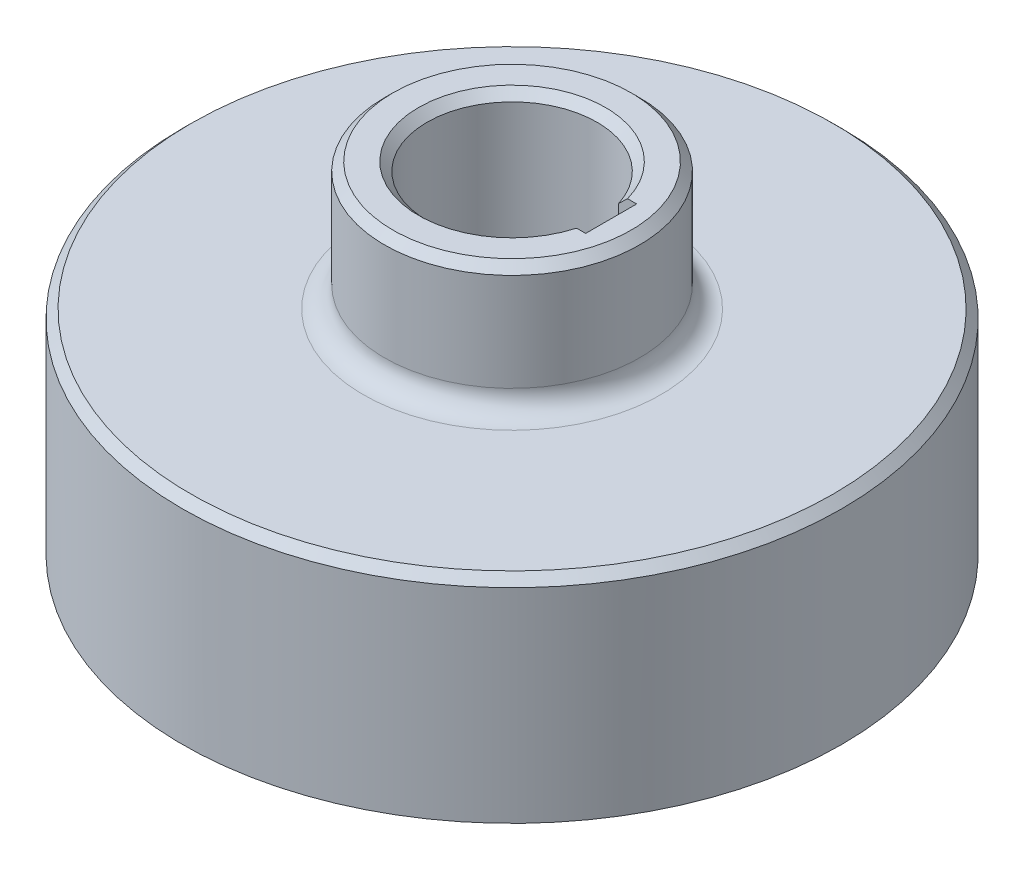
SolidWorks part; units mm, degrees
material "1.0060 (E335)"
ref_plane "Front Plane" through (0, 0, 0) normal (0, 0, 1) x (1, 0, 0)
ref_plane "Top Plane" through (0, 0, 0) normal (0, 1, 0) x (1, 0, 0)
ref_plane "Right Plane" through (0, 0, 0) normal (1, 0, 0) x (0, 0, -1)
sketch "Sketch1" plane through (0, 0, 0) normal (0, 0, 1) x (1, 0, 0)
  line L0 (0, -1292.3904) -> (0, 63327.1275) construction
  line L1 (20, 80) -> (30, 80)
  line L2 (30, 80) -> (30, 50)
  line L3 (30, 50) -> (77.5, 50)
  line L4 (77.5, 50) -> (77.5, 0)
  line L5 (77.5, 0) -> (63, 0)
  line L7 (70, 40) -> (25, 40)
  line L8 (20, 45) -> (20, 80)
  line L9 (70, 40) -> (70, 35)
  line L10 (63, 0) -> (63, 35)
  line L11 (63, 35) -> (70, 35)
  line L12 (25, 40) -> (25, 45)
  line L13 (25, 45) -> (20, 45)
  dimension "D1" = 40
  dimension "D2" = 5
  dimension "D3" = 5
  dimension "D4" = 155
  dimension "D5" = 10
  dimension "D6" = 60
  dimension "D7" = 126
  dimension "D8" = 140
  dimension "D9" = 35
  dimension "D10" = 40
  dimension "D11" = 5
revolve "Revolve1" add sketch "Sketch1" angle 360 about L0
fillet "Fillet1" radius 1.5 1 edges at (70, 40, 0)
sketch "Sketch2" plane through (0, 0, 0) normal (0, -1, 0) x (1, 0, 0)
  line L0 (0, -1000) -> (0, 49000) construction
  line L1 (-6.125, 68.8) -> (6.125, 68.8)
  line L2 (6.125, 68.8) -> (6.125, 62.7016)
  line L3 (-6.125, 68.8) -> (-6.125, 62.7016)
  circle A0 centre (0, 0) radius 63 construction
  arc A1 (6.125, 62.7016) -> (-6.125, 62.7016) centre (0, 0) ccw
  point P5 (0, 68.8)
  dimension "D1" = 12.25
  dimension "D2" = 68.8
extrude "Cut-Extrude1" cut sketch "Sketch2" against normal up to surface (35 mm away) up to face at (63, 35, 0)
fillet "Fillet2" radius 2 2 edges at (6.125, 17.5, 62.7016) (-6.125, 17.5, 62.7016)
pattern_circular "CirPattern1" count 6 over 360 about axis through (0, 0, 0) along (0, 1, 0) of "Cut-Extrude1", "Fillet2"
fillet "Fillet3" radius 5 1 edges at (30, 50, 0)
chamfer "Chamfer1" distance 2 angle 45 3 edges at (30, 80, 0) (77.5, 50, 0) (20, 80, 0)
chamfer "Chamfer3" distance 1 angle 45 2 edges at (25, 40, 0) (20, 45, 0)
ref_plane "Plane1" through (23.3, 0, 0) normal (1, 0, 0) x (0, 0, -1)
sketch "Sketch3" plane through (23.3, 0, 0) normal (1, 0, 0) x (0, 0, -1)
  line L0 (28, 80) -> (-28, 80) construction
  line L1 (-6, 80) -> (6, 80)
  line L2 (-6, 80) -> (-6, 45)
  line L3 (-6, 45) -> (6, 45)
  line L4 (6, 80) -> (6, 45)
  line L6 (-21, 45) -> (21, 45) construction
  point P6 (0, 80)
  dimension "D1" = 12
extrude "Cut-Extrude2" cut sketch "Sketch3" against normal up to next
sketch "Sketch6" plane through (0, 0, 0) normal (0, 0, 1) x (1, 0, 0)
  line L0 (-70.25, -967.9081) -> (-70.25, 49032.0919) construction
  line L3 (-77.5, 0) -> (-63, 0) construction
  line L5 (-67.75, 0) -> (-67.75, 10)
  line L6 (-67.75, 10) -> (-70.25, 11.4434)
  line L7 (-70.25, 11.4434) -> (-70.25, 0)
  line L8 (-70.25, 0) -> (-67.75, 0)
  point P1 (-63, 0)
  point P3 (-75.5, 0)
  point P6 (-77.5, 0)
  point P11 (-70.25, 0)
  dimension "D1" = 60
  dimension "D2" = 5
  dimension "D3" = 10
revolve "Cut-Revolve1" cut sketch "Sketch6" angle 360 about L0
chamfer "Chamfer4" distance 0.5 angle 45 1 edges at (-70.25, 0, -2.5)
pattern_circular "CirPattern2" count 6 over 360 about axis through (0, 0, 0) along (0, 1, 0) of "Cut-Revolve1", "Chamfer4"
